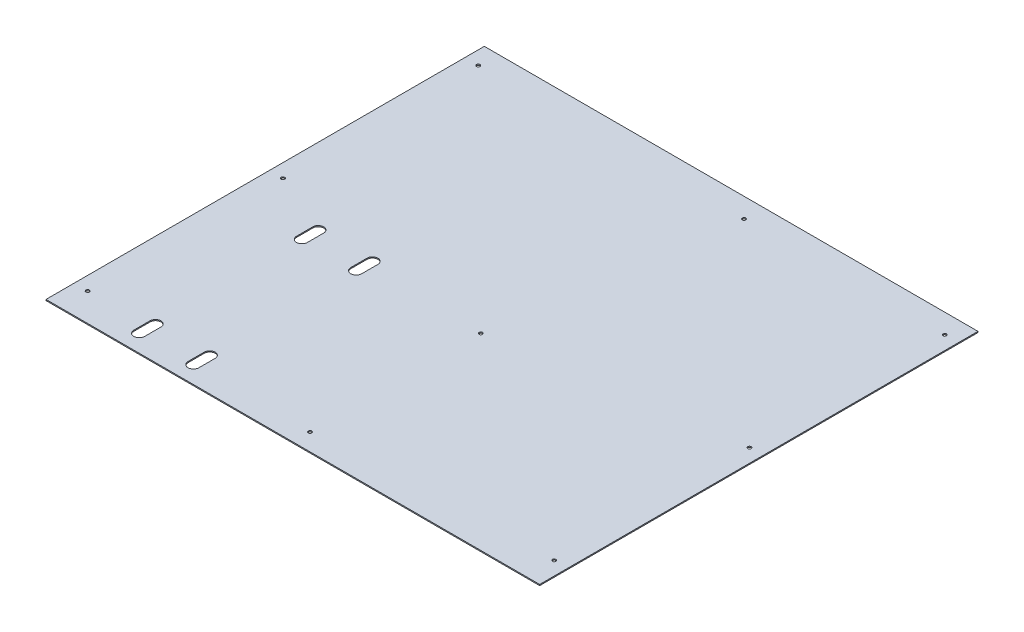
SolidWorks part; units mm, degrees
material "acero"
ref_plane "Alzado" through (0, 0, 0) normal (0, 0, 1) x (1, 0, 0)
ref_plane "Planta" through (0, 0, 0) normal (0, 1, 0) x (1, 0, 0)
ref_plane "Vista lateral" through (0, 0, 0) normal (1, 0, 0) x (0, 0, -1)
sketch "Croquis1" plane through (0, 0, 0) normal (0, 1, 0) x (1, 0, 0)
  line L1 (-227.5, -204.5) -> (227.5, -204.5)
  line L2 (-227.5, -204.5) -> (-227.5, 204.5)
  line L3 (-227.5, 204.5) -> (227.5, 204.5)
  line L4 (227.5, -204.5) -> (227.5, 204.5)
  line L5 (-227.5, -204.5) -> (227.5, 204.5) construction
  line L6 (-227.5, 204.5) -> (227.5, -204.5) construction
  point P0 (0, 0)
  dimension "D1" = 455
  dimension "D2" = 409
extrude "Saliente-Extruir1" add sketch "Croquis1" along normal blind 1
sketch "Croquis2" plane through (0, 0, 0) normal (0, -1, 0) x (1, 0, 0)
  line L0 (-227.5, 204.5) -> (227.5, 204.5) construction
  line L1 (227.5, 204.5) -> (227.5, -204.5) construction
  line L2 (0, 0) -> (0, -204.5) construction
  line L3 (227.5, -204.5) -> (-227.5, -204.5) construction
  circle A0 centre (-215, 178.6) radius 1.6
  circle A1 centre (-215, -181.4) radius 1.6
  circle A2 centre (215, -181.4) radius 1.6
  circle A3 centre (215, 178.6) radius 1.6
  circle A4 centre (0, 31.25) radius 1.6
  dimension "D1" = 3.2
  dimension "D2" = 173.25
  dimension "D5" = 360
  dimension "D3" = 227.5
  dimension "D4" = 430
  dimension "D7" = 25.9
extrude "Cortar-Extruir1" cut sketch "Croquis2" against normal up to next
sketch "Croquis3" plane through (0, 0, 0) normal (0, -1, 0) x (1, 0, 0)
  line L0 (-227.5, 204.5) -> (227.5, 204.5) construction
  line L1 (-227.5, -204.5) -> (-227.5, 204.5) construction
  circle A0 centre (-157.5, 38.6) radius 5
  circle A1 centre (-107.5, 38.6) radius 5
  circle A2 centre (-107.5, 188.6) radius 5
  circle A3 centre (-157.5, 188.6) radius 5
  dimension "D1" = 10
  dimension "D3" = 50
  dimension "D6" = 70
  dimension "D2" = 50
  dimension "D4" = 150
  dimension "D5" = 15.9
extrude "Cortar-Extruir2" cut sketch "Croquis3" against normal up to next
sketch "Croquis4" plane through (0, 0, 0) normal (0, -1, 0) x (1, 0, 0)
  line L0 (-215, -181.4) -> (215, -181.4) construction
  line L1 (215, -181.4) -> (215, 178.6) construction
  line L2 (215, 178.6) -> (-215, 178.6) construction
  line L3 (-215, 178.6) -> (-215, -181.4) construction
  circle A0 centre (-215, -1.4) radius 1.6
  circle A1 centre (215, -1.4) radius 1.6
  circle A2 centre (0, 188.6) radius 1.6
  circle A3 centre (30, -181.4) radius 1.6
  circle A4 centre (0, 31.25) radius 1.6 construction
  point P12 (0, -181.4)
  point P13 (0, 178.6)
  dimension "D1" = 30
  dimension "D2" = 10
extrude "Cortar-Extruir3" cut sketch "Croquis4" against normal up to next
other "Mover cara1" face at (0, 0.5, -204.5) parameters "D1"=5
sketch "Croquis5" plane through (0, 0, 0) normal (0, -1, 0) x (1, 0, 0)
  line L0 (-157.5, 173.6) -> (-157.5, 188.6) construction
  line L1 (-162.5, 173.6) -> (-162.5, 188.6)
  line L2 (-152.5, 173.6) -> (-152.5, 188.6)
  line L3 (-107.5, 173.6) -> (-107.5, 188.6) construction
  line L4 (-112.5, 173.6) -> (-112.5, 188.6)
  line L5 (-102.5, 173.6) -> (-102.5, 188.6)
  line L6 (-157.5, 23.6) -> (-157.5, 38.6) construction
  line L7 (-162.5, 23.6) -> (-162.5, 38.6)
  line L8 (-152.5, 23.6) -> (-152.5, 38.6)
  line L9 (-107.5, 23.6) -> (-107.5, 38.6) construction
  line L10 (-112.5, 23.6) -> (-112.5, 38.6)
  line L11 (-102.5, 23.6) -> (-102.5, 38.6)
  arc A0 (-162.5, 173.6) -> (-152.5, 173.6) centre (-157.5, 173.6) ccw
  arc A1 (-152.5, 188.6) -> (-162.5, 188.6) centre (-157.5, 188.6) ccw
  circle A2 centre (-157.5, 188.6) radius 5 construction
  arc A3 (-112.5, 173.6) -> (-102.5, 173.6) centre (-107.5, 173.6) ccw
  arc A4 (-102.5, 188.6) -> (-112.5, 188.6) centre (-107.5, 188.6) ccw
  arc A5 (-162.5, 23.6) -> (-152.5, 23.6) centre (-157.5, 23.6) ccw
  arc A6 (-152.5, 38.6) -> (-162.5, 38.6) centre (-157.5, 38.6) ccw
  arc A7 (-112.5, 23.6) -> (-102.5, 23.6) centre (-107.5, 23.6) ccw
  arc A8 (-102.5, 38.6) -> (-112.5, 38.6) centre (-107.5, 38.6) ccw
  point P2 (-157.5, 181.1)
  point P12 (-107.5, 181.1)
  point P19 (-157.5, 31.1)
  point P26 (-107.5, 31.1)
  dimension "D1" = 15
extrude "Cortar-Extruir4" cut sketch "Croquis5" against normal blind 10
